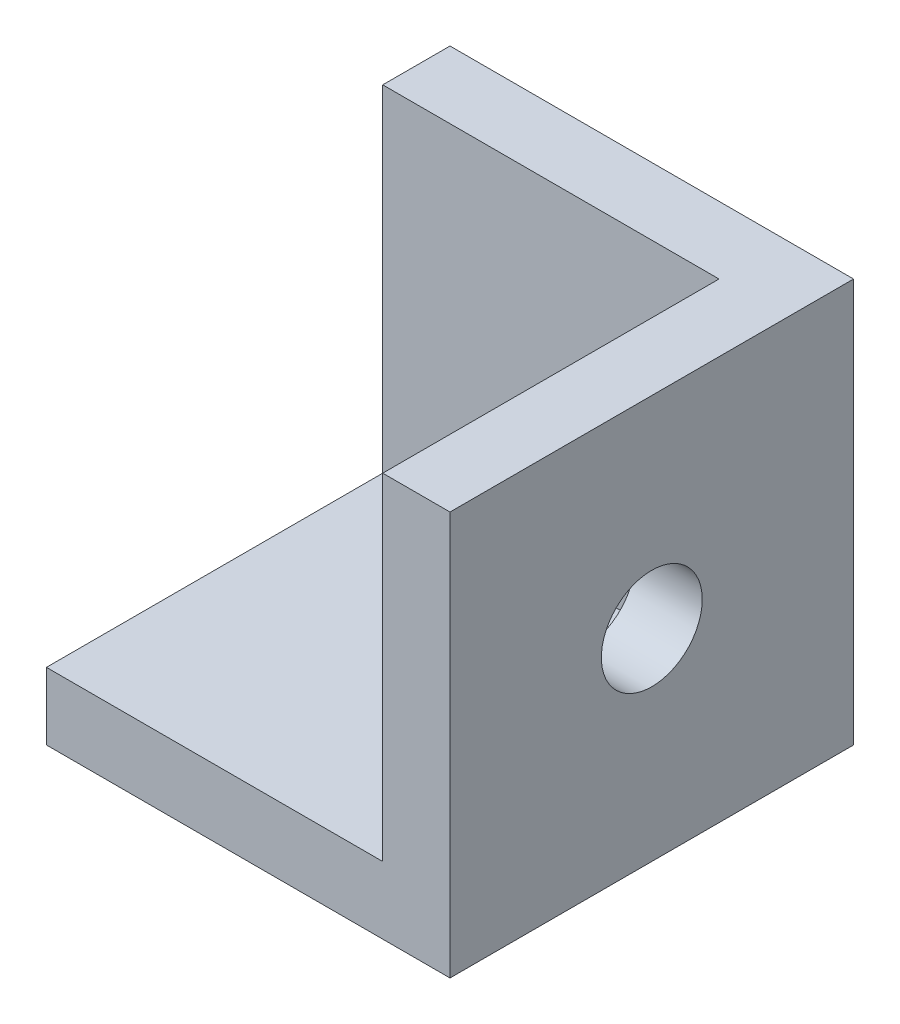
SolidWorks part; units mm, degrees
ref_plane "Front Plane" through (0, 0, 0) normal (0, 0, 1) x (1, 0, 0)
ref_plane "Top Plane" through (0, 0, 0) normal (0, 1, 0) x (1, 0, 0)
ref_plane "Right Plane" through (0, 0, 0) normal (1, 0, 0) x (0, 0, -1)
sketch "Sketch2" plane through (0, 0, 0) normal (1, 0, 0) x (0, 0, -1)
  line L0 (0, 0) -> (0, 19.05)
  line L1 (0, 0) -> (-19.05, 0)
  line L2 (-3.175, 3.175) -> (-19.05, 3.175)
  line L3 (-3.175, 3.175) -> (-3.175, 19.05)
  line L4 (-3.175, 19.05) -> (0, 19.05)
  line L5 (-19.05, 3.175) -> (-19.05, 0)
  dimension "D1" = 19.05
  dimension "D2" = 3.175
extrude "Boss-Extrude1" add sketch "Sketch2" along normal blind 19.05
sketch "Sketch3" plane through (19.05, 0, 0) normal (1, 0, 0) x (0, 0, -1)
  line L0 (-19.05, 3.175) -> (-19.05, 0) construction
  line L1 (0, 0) -> (-19.05, 0)
  line L2 (0, 0) -> (0, 19.05)
  line L3 (0, 19.05) -> (-19.05, 19.05)
  line L4 (-19.05, 0) -> (-19.05, 19.05)
  line L5 (0, 19.05) -> (-3.175, 19.05) construction
extrude "Boss-Extrude2" add sketch "Sketch3" against normal blind 3.175
sketch "Sketch4" plane through (19.05, 0, 0) normal (1, 0, 0) x (0, 0, -1)
  line L0 (-19.05, 0) -> (0, 0) construction
  line L1 (0, 0) -> (0, 19.05) construction
  circle A0 centre (-9.525, 9.525) radius 2.3813
  point P4 (-9.525, 0)
  point P7 (0, 9.525)
  dimension "D1" = 4.7625
extrude "Cut-Extrude1" cut sketch "Sketch4" against normal through all
